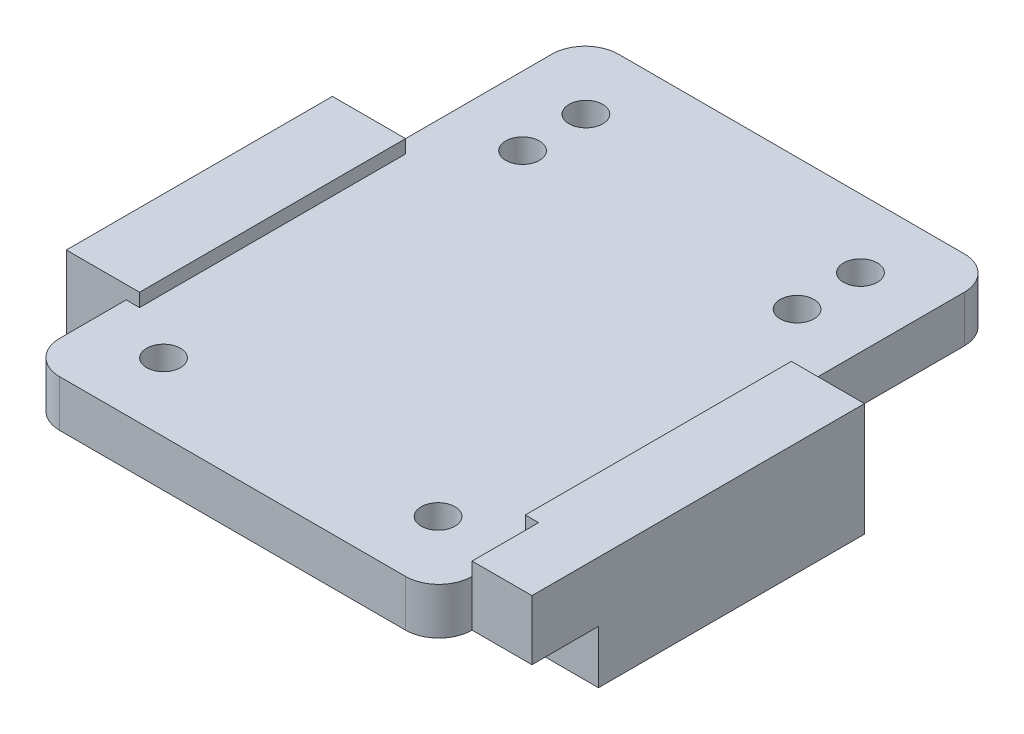
SolidWorks part; units mm, degrees
material "ABS"
ref_plane "정면" through (0, 0, 0) normal (0, 0, 1) x (1, 0, 0)
ref_plane "윗면" through (0, 0, 0) normal (0, 1, 0) x (1, 0, 0)
ref_plane "우측면" through (0, 0, 0) normal (1, 0, 0) x (0, 0, -1)
sketch "스케치2" plane through (0, 0, 0) normal (0, 1, 0) x (1, 0, 0)
  line L1 (31, 42) -> (-31, 42)
  line L2 (31, 42) -> (31, -42)
  line L3 (31, -42) -> (-31, -42)
  line L4 (-31, 42) -> (-31, -42)
  line L5 (31, 42) -> (-31, -42) construction
  line L6 (31, -42) -> (-31, 42) construction
  line L7 (28, -39.5) -> (-28, -39.5) construction
  line L8 (28, -39.5) -> (28, 39.5) construction
  line L9 (28, 39.5) -> (-28, 39.5) construction
  line L10 (-28, -39.5) -> (-28, 39.5) construction
  line L11 (28, -39.5) -> (-28, 39.5) construction
  line L12 (28, 39.5) -> (-28, -39.5) construction
  point P0 (0, 0)
  point P6 (0, 0)
  dimension "D1" = 62
  dimension "D2" = 84
  dimension "D3" = 79
  dimension "D4" = 56
extrude "보스-돌출1" add sketch "스케치2" along normal blind 7
sketch "스케치4" plane through (0, 0, 0) normal (0, -1, 0) x (1, 0, 0)
  line L0 (0, 42) -> (0, -42) construction
  line L7 (-31, 42) -> (31, 42) construction
  line L8 (31, -42) -> (-31, -42) construction
  line L9 (20.6375, 31.75) -> (-20.6375, -31.75) construction
  circle A0 centre (20.6375, 31.75) radius 2.54
  circle A1 centre (20.6375, -22.225) radius 2.54
  circle A2 centre (20.6375, -31.75) radius 2.54
  circle A3 centre (-20.6375, -31.75) radius 2.54
  circle A4 centre (-20.6375, -22.225) radius 2.54
  circle A5 centre (-20.6375, 31.75) radius 2.54
  point P0 (0, 0)
  dimension "D1" = 5.08
  dimension "D2" = 41.275
  dimension "D3" = 53.975
  dimension "D4" = 63.5
extrude "컷-돌출1" cut sketch "스케치4" against normal through all and the other way through all
fillet "필렛1" radius 5 2 edges at (31, 3.5, -42) (-31, 3.5, -42)
fillet "필렛4" radius 5 2 edges at (31, 3.5, 42) (-31, 3.5, 42)
surface "Surface-Offset1" [suppressed] parameters "D1"=0
other "SurfaceCut1" [suppressed]
sketch "스케치5" plane through (0, 0, 0) normal (0, -1, 0) x (1, 0, 0)
  line L0 (-40, 27) -> (-40, -13)
  line L1 (29, 27) -> (40, 27)
  line L2 (29, 27) -> (29, -13)
  line L3 (29, -13) -> (40, -13)
  line L4 (40, 27) -> (40, -13)
  line L5 (-26, 42) -> (26, 42) construction
  line L6 (0, 42) -> (0, -42) construction
  line L7 (31, 42) -> (-31, 42) construction
  line L8 (31, -42) -> (-31, -42) construction
  line L9 (-29, -13) -> (-40, -13)
  line L10 (-29, 27) -> (-29, -13)
  line L11 (-29, 27) -> (-40, 27)
  dimension "D1" = 11
  dimension "D2" = 40
  dimension "D3" = 15
  dimension "D4" = 29
extrude "보스-돌출2" add sketch "스케치5" along normal blind 8 and the other way offset from surface (9 mm away) 2 other way up to face at (20.6375, 7, -24.765)
sketch "스케치11" plane through (31, 0, 0) normal (1, 0, 0) x (0, 0, -1)
  line L3 (-27, 0) -> (-27, 7)
  line L4 (-37, 0) -> (-27, 0)
  line L5 (-27, 0) -> (-27, 9)
  line L7 (-37, 7) -> (-37, 0)
  line L8 (-37, 0) -> (-27, 0)
  line L9 (-27, 7) -> (-37, 7)
  line L10 (-27, 9) -> (-37, 9)
  line L11 (-37, 9) -> (-37, 0)
  dimension "D1" = 0
extrude "보스-돌출3" add sketch "스케치11" along normal blind 9
